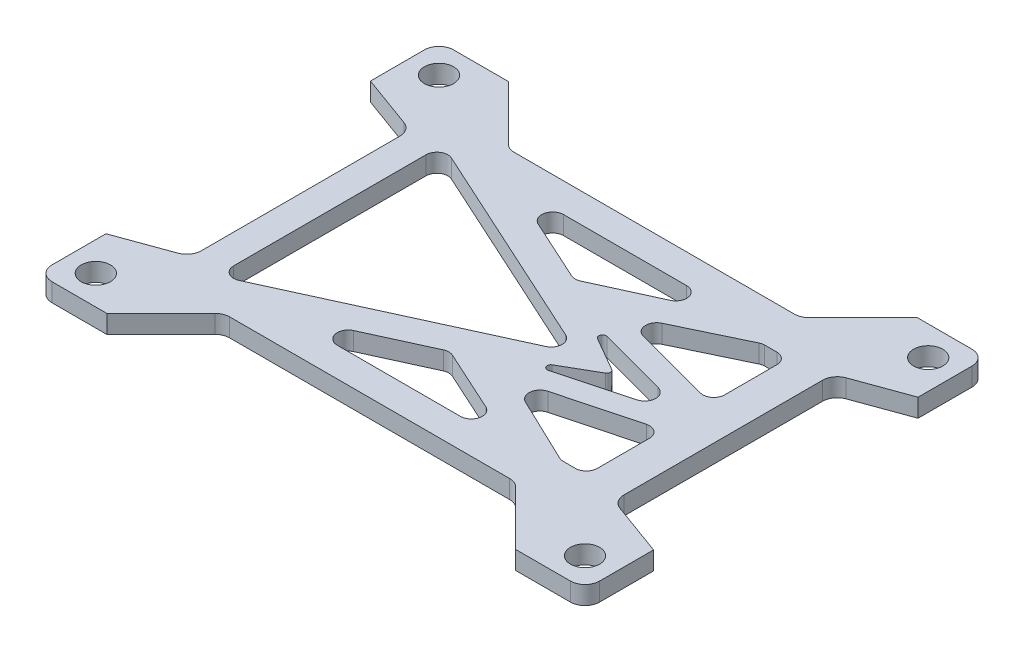
SolidWorks part; units mm, degrees
material "ABS"
ref_plane "前视基准面" through (0, 0, 0) normal (0, 0, 1) x (1, 0, 0)
ref_plane "上视基准面" through (0, 0, 0) normal (0, 1, 0) x (1, 0, 0)
ref_plane "右视基准面" through (0, 0, 0) normal (1, 0, 0) x (0, 0, -1)
sketch "草图2" plane through (0, 0, 0) normal (0, 1, 0) x (1, 0, 0)
  line L1 (-37.5, 27.5) -> (-28, 27.5)
  line L2 (-37.5, 27.5) -> (-37.5, 18.1119)
  line L3 (-37.5, -27.5) -> (-28, -27.5)
  line L4 (37.5, 27.5) -> (37.5, 18.1119)
  line L5 (-37.5, 27.5) -> (37.5, -27.5) construction
  line L6 (-37.5, -27.5) -> (37.5, 27.5) construction
  line L7 (-28.95, 19.5) -> (28.95, 19.5) construction
  line L8 (-28.95, 19.5) -> (-28.95, -19.5) construction
  line L9 (-28.95, -19.5) -> (28.95, -19.5) construction
  line L10 (28.95, 19.5) -> (28.95, -19.5) construction
  line L11 (-28.95, 19.5) -> (28.95, -19.5) construction
  line L12 (-28.95, -19.5) -> (28.95, 19.5) construction
  line L13 (0, -27.5) -> (0, 27.5) construction
  line L14 (15.3234, 15.5) -> (0, 8.5)
  line L15 (0, 8.5) -> (-15.3234, 15.5)
  line L16 (-24.95, 15.5) -> (-24.95, -15.5)
  line L17 (-24.95, -15.5) -> (8.9804, 0)
  line L18 (8.9804, 0) -> (-24.95, 15.5)
  line L19 (-37.5, 0) -> (37.5, 0) construction
  line L20 (-15.3234, 15.5) -> (15.3234, 15.5)
  line L21 (-15.3234, -15.5) -> (15.3234, -15.5)
  line L22 (0, -8.5) -> (-15.3234, -15.5)
  line L23 (15.3234, -15.5) -> (0, -8.5)
  line L24 (5.3201, 5) -> (13.9804, 0)
  line L25 (13.9804, 0) -> (5.3201, -5)
  line L26 (5.3201, -5) -> (23.9804, 0)
  line L27 (23.9804, 0) -> (5.3201, 5)
  line L28 (-28, 27.5) -> (-20, 19.5)
  line L29 (-20, 19.5) -> (20, 19.5)
  line L30 (20, 19.5) -> (28, 27.5)
  line L31 (28, 27.5) -> (37.5, 27.5)
  line L32 (-37.5, 18.1119) -> (-28.95, 15)
  line L33 (-28.95, 15) -> (-28.95, -15)
  line L34 (-28.95, -15) -> (-37.5, -18.1119)
  line L35 (28.95, -15) -> (37.5, -18.1119)
  line L36 (28.95, 15) -> (28.95, -15)
  line L37 (37.5, 18.1119) -> (28.95, 15)
  line L38 (20, -19.5) -> (28, -27.5)
  line L39 (-20, -19.5) -> (20, -19.5)
  line L40 (-28, -27.5) -> (-20, -19.5)
  line L41 (-37.5, -18.1119) -> (-37.5, -27.5)
  line L42 (37.5, -18.1119) -> (37.5, -27.5)
  line L43 (28, -27.5) -> (37.5, -27.5)
  line L44 (7.4997, 7.582) -> (20.4785, 13.7938)
  line L45 (20.4785, 13.7938) -> (23.9804, 13.7938)
  line L46 (23.9804, 13.7938) -> (23.9804, 3.2066)
  line L47 (23.9804, 3.2066) -> (7.4997, 7.582)
  line L48 (23.9804, -13.7938) -> (23.9804, -3.2066)
  line L49 (20.4785, -13.7938) -> (23.9804, -13.7938)
  line L50 (7.4997, -7.582) -> (20.4785, -13.7938)
  line L51 (23.9804, -3.2066) -> (7.4997, -7.582)
  point P0 (0, 0)
  point P6 (0, 0)
  dimension "D1" = 55
  dimension "D2" = 75
  dimension "D3" = 39
  dimension "D4" = 57.9
  dimension "D5" = 4
  dimension "D6" = 4
  dimension "D7" = 4
  dimension "D8" = 7
  dimension "D9" = 10
  dimension "D10" = 5
  dimension "D11" = 15
  dimension "D12" = 60
  dimension "D13" = 40
  dimension "D14" = 30
  dimension "D15" = 110
extrude "凸台-拉伸1" add sketch "草图2" along normal blind 2.5
fillet "圆角2" radius 1.5 18 edges at (23.9804, 1.25, 0) (23.9804, 1.25, -3.2066) (20.4785, 1.25, -13.7938) (7.4997, 1.25, -7.582) (23.9804, 1.25, -13.7938) (23.9804, 1.25, 3.2066) (7.4997, 1.25, 7.582) (20.4785, 1.25, 13.7938) (23.9804, 1.25, 13.7938) (-15.3234, 1.25, 15.5) (0, 1.25, 8.5) (15.3234, 1.25, 15.5) (0, 1.25, -8.5) (-15.3234, 1.25, -15.5) (15.3234, 1.25, -15.5) (-24.95, 1.25, 15.5) (-24.95, 1.25, -15.5) (8.9804, 1.25, 0)
fillet "圆角3" radius 0.5 3 edges at (13.9804, 1.25, 0) (5.3201, 1.25, -5) (5.3201, 1.25, 5)
sketch "草图3" plane through (0, 2.5, 0) normal (0, 1, 0) x (1, 0, 0)
  line L0 (-33.5, 0) -> (0, 0) construction
  line L1 (-33.5, 23.5) -> (33.5, 23.5) construction
  line L2 (-33.5, 23.5) -> (-33.5, -23.5) construction
  line L3 (-33.5, -23.5) -> (33.5, -23.5) construction
  line L4 (33.5, 23.5) -> (33.5, -23.5) construction
  line L5 (-33.5, 23.5) -> (33.5, -23.5) construction
  line L6 (-33.5, -23.5) -> (33.5, 23.5) construction
  circle A0 centre (-33.5, -23.5) radius 2
  circle A1 centre (33.5, -23.5) radius 2
  circle A2 centre (33.5, 23.5) radius 2
  circle A3 centre (-33.5, 23.5) radius 2
  point P0 (0, 0)
  dimension "D1" = 4
  dimension "D2" = 47
  dimension "D3" = 67
extrude "切除-拉伸1" cut sketch "草图3" against normal through all
fillet "圆角4" radius 2 12 edges at (37.5, 1.25, -27.5) (37.5, 1.25, 27.5) (-37.5, 1.25, 27.5) (-37.5, 1.25, -27.5) (-28.95, 1.25, -15) (-20, 1.25, -19.5) (20, 1.25, -19.5) (28.95, 1.25, -15) (28.95, 1.25, 15) (20, 1.25, 19.5) (-20, 1.25, 19.5) (-28.95, 1.25, 15)
